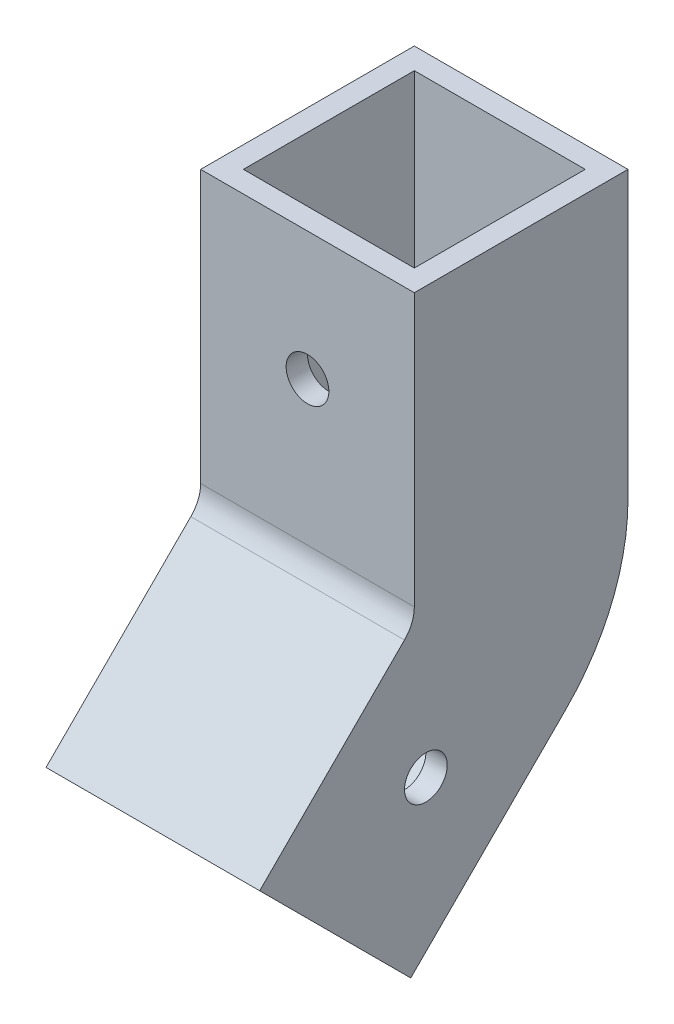
SolidWorks part; units mm, degrees
material "6061-T6 (SS)"
ref_plane "Front Plane" through (0, 0, 0) normal (0, 0, 1) x (1, 0, 0)
ref_plane "Top Plane" through (0, 0, 0) normal (0, 1, 0) x (1, 0, 0)
ref_plane "Right Plane" through (0, 0, 0) normal (1, 0, 0) x (0, 0, -1)
sketch "Sketch1" plane through (0, 0, 0) normal (1, 0, 0) x (0, 0, -1)
  line L1 (15.875, -42.5) -> (-15.875, -42.5) construction
  line L2 (15.875, -42.5) -> (15.875, 42.5) construction
  line L3 (15.875, 42.5) -> (-15.875, 42.5)
  line L4 (-15.875, -42.5) -> (-15.875, 42.5) construction
  line L5 (15.875, -42.5) -> (-15.875, 42.5) construction
  line L6 (15.875, 42.5) -> (-15.875, -42.5) construction
  line L7 (-15.875, 42.5) -> (-15.875, 0)
  line L8 (15.875, 42.5) -> (15.875, 0)
  line L10 (-16.4053, -45.4316) -> (-38.856, -22.981)
  line L11 (-38.856, -22.981) -> (-15.875, 0)
  line L12 (-16.4053, -45.4316) -> (6.5756, -22.4506)
  arc A0 (15.875, 0) -> (6.5756, -22.4506) centre (-15.875, 0) cw
  point P0 (0, 0)
  dimension "D1" = 31.75
  dimension "D2" = 85
  dimension "D3" = 135
  dimension "D4" = 32.5
extrude "Boss-Extrude1" add sketch "Sketch1" along normal blind 31.75
sketch "Sketch3" plane through (0, 0, 0) normal (-1, 0, 0) x (0, 0, 1)
  line L30 (16.4053, -40.9415) -> (34.3658, -22.981)
  line L31 (-4.3306, -20.2056) -> (16.4053, -40.9415)
  line L32 (34.3658, -22.981) -> (12.7, -1.3151)
  line L33 (12.7, -1.3151) -> (12.7, 39.325)
  line L34 (-12.7, 39.325) -> (-12.7, 0)
  line L35 (12.7, 39.325) -> (-12.7, 39.325)
  line L36 (16.4053, -40.9415) -> (34.3658, -22.981)
  line L37 (-4.3306, -20.2056) -> (16.4053, -40.9415)
  line L38 (34.3658, -22.981) -> (12.7, -1.3151)
  line L39 (12.7, -1.3151) -> (12.7, 39.325)
  line L40 (-12.7, 39.325) -> (-12.7, 0)
  line L41 (12.7, 39.325) -> (-12.7, 39.325)
  arc A5 (-12.7, 0) -> (-4.3306, -20.2056) centre (15.875, 0) ccw
  arc A6 (-12.7, 0) -> (-4.3306, -20.2056) centre (15.875, 0) ccw
  dimension "D1" = 3.175
extrude "Cut-Extrude2" cut sketch "Sketch3" against normal offset from surface (25.4 mm away) 3.175 from offset 3.175 up to face at (31.75, -0.9697, 6.6361) offset against normal yes
sketch "Sketch4" plane through (0, 42.5, 0) normal (0, 1, 0) x (1, 0, 0)
  line L14 (3.175, -12.7) -> (28.575, -12.7)
  line L15 (3.175, 12.7) -> (3.175, -12.7)
  line L16 (28.575, -12.7) -> (28.575, 12.7)
  line L17 (28.575, 12.7) -> (3.175, 12.7)
  line L18 (3.175, -12.7) -> (28.575, -12.7)
  line L19 (3.175, 12.7) -> (3.175, -12.7)
  line L20 (28.575, -12.7) -> (28.575, 12.7)
  line L21 (28.575, 12.7) -> (3.175, 12.7)
  dimension "D1" = 3.175
extrude "Cut-Extrude3" cut sketch "Sketch4" against normal blind 3.175
sketch "Sketch6" plane through (0, -30.9185, 30.9185) normal (0, -0.7071, 0.7071) x (1, 0, 0)
  line L14 (3.175, 8.0503) -> (3.175, -17.3497)
  line L15 (3.175, -17.3497) -> (28.575, -17.3497)
  line L16 (28.575, -17.3497) -> (28.575, 8.0503)
  line L17 (28.575, 8.0503) -> (3.175, 8.0503)
  line L18 (3.175, 8.0503) -> (3.175, -17.3497)
  line L19 (3.175, -17.3497) -> (28.575, -17.3497)
  line L20 (28.575, -17.3497) -> (28.575, 8.0503)
  line L21 (28.575, 8.0503) -> (3.175, 8.0503)
  dimension "D1" = 3.175
extrude "Cut-Extrude5" cut sketch "Sketch6" against normal blind 3.175
fillet "Fillet1" radius 5 2 edges at (15.875, -1.3151, 12.7) (15.875, 0, 15.875)
sketch "Sketch8" plane through (0, 0, -15.875) normal (0, 0, -1) x (-1, 0, 0)
  line L1 (-31.75, 42.5) -> (0, 42.5) construction
  line L2 (-15.875, 42.5) -> (-15.875, 0) construction
  line L3 (-31.75, 0) -> (0, 0) construction
  circle A0 centre (-15.875, 23.45) radius 3.175
  dimension "D2" = 6.35
  dimension "D3" = 19.05
extrude "Cut-Extrude6" cut sketch "Sketch8" against normal up to surface (31.75 mm away) up to face at (15.875, 22.2855, 15.875)
sketch "Sketch9" plane through (31.75, 0, 0) normal (1, 0, 0) x (0, 0, -1)
  line L0 (-16.4053, -45.4316) -> (6.5756, -22.4506) construction
  line L1 (-38.856, -22.981) -> (-16.4053, -45.4316) construction
  circle A0 centre (-14.1603, -20.7359) radius 3.175
  dimension "D2" = 6.35
  dimension "D1" = 15.875
  dimension "D3" = 19.05
extrude "Cut-Extrude7" cut sketch "Sketch9" against normal up to surface (31.75 mm away) up to face at (0, -0.7909, 7.9301)
